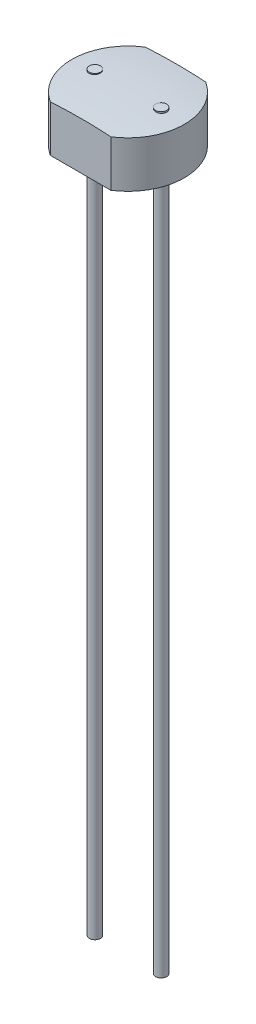
SolidWorks part; units mm, degrees
ref_plane "Plan de face" through (0, 0, 0) normal (0, 0, 1) x (1, 0, 0)
ref_plane "Plan de dessus" through (0, 0, 0) normal (0, 1, 0) x (1, 0, 0)
ref_plane "Plan de droite" through (0, 0, 0) normal (1, 0, 0) x (0, 0, -1)
sketch "Esquisse1" plane through (0, 0, 0) normal (0, 1, 0) x (1, 0, 0)
  line L0 (-1.3711, -2.15) -> (1.3711, -2.15)
  line L1 (-1.3711, 2.15) -> (1.3711, 2.15)
  arc A0 (-1.3711, -2.15) -> (-1.3711, 2.15) centre (0, 0) cw
  arc A1 (1.3711, 2.15) -> (1.3711, -2.15) centre (0, 0) cw
  point P6 (-1.2041, -1.5481)
  point P7 (1.4662, -2.0948)
  point P8 (1.0941, 2.247)
  point P9 (1.7016, -2.387)
  point P10 (0, 0)
  point P12 (-0.9981, -2.053)
  point P13 (-2.55, 0)
  point P14 (2.55, 0)
  point P15 (0, 0)
  point P16 (0, 0)
  dimension "D1" = 4.3
  dimension "D2" = 5.1
extrude "Boss.-Extru.1" add sketch "Esquisse1" along normal blind 2.1
sketch "Esquisse2" plane through (0, 0, 0) normal (0, 0, 1) x (1, 0, 0)
  line L0 (0, 2.1) -> (0, 2.25)
  line L1 (-1.3711, 2.1) -> (1.3711, 2.1) construction
  line L2 (-2.55, 2.1) -> (0, 2.1)
  arc A0 (0, 2.25) -> (-2.55, 2.1) centre (0, -19.5) ccw
  dimension "D1" = 0.15
revolve "Révolution1" add sketch "Esquisse2" angle 360 about L0
ref_plane "Plan1" through (0, 2.25, 0) normal (0, 1, 0) x (1, 0, 0)
sketch "Esquisse3" plane through (0, 2.1, 0) normal (0, -1, 0) x (1, 0, 0)
  line L0 (-1.3711, -2.15) -> (1.3711, -2.15)
  line L1 (1.3711, -2.15) -> (1.3711, -2.6225)
  line L2 (1.3711, -2.6225) -> (-1.3711, -2.6225)
  line L3 (-1.3711, -2.6225) -> (-1.3711, -2.15)
  line L4 (-1.3711, 2.15) -> (-1.3711, 2.6363)
  line L5 (-1.3711, 2.6363) -> (1.3078, 2.6363)
  line L6 (1.3078, 2.6363) -> (1.3711, 2.15)
  line L7 (-1.3711, 2.15) -> (1.3711, 2.15) construction
  line L8 (1.3711, 2.15) -> (-1.3711, 2.15)
  arc A0 (1.3711, 2.15) -> (-1.3711, 2.15) centre (0, 0) ccw construction
extrude "Enlèv. mat.-Extru.1" cut sketch "Esquisse3" against normal blind 2.1
sketch "Esquisse5" plane through (0, 2.25, 0) normal (0, 1, 0) x (1, 0, 0)
  circle A0 centre (-1.5, 0) radius 0.25
  circle A1 centre (1.5, 0) radius 0.25
  dimension "D1" = 0.5
  dimension "D2" = 0.5
  dimension "D3" = 1.5
  dimension "D4" = 1.5
extrude "Boss.-Extru.2" add sketch "Esquisse5" against normal blind 34
